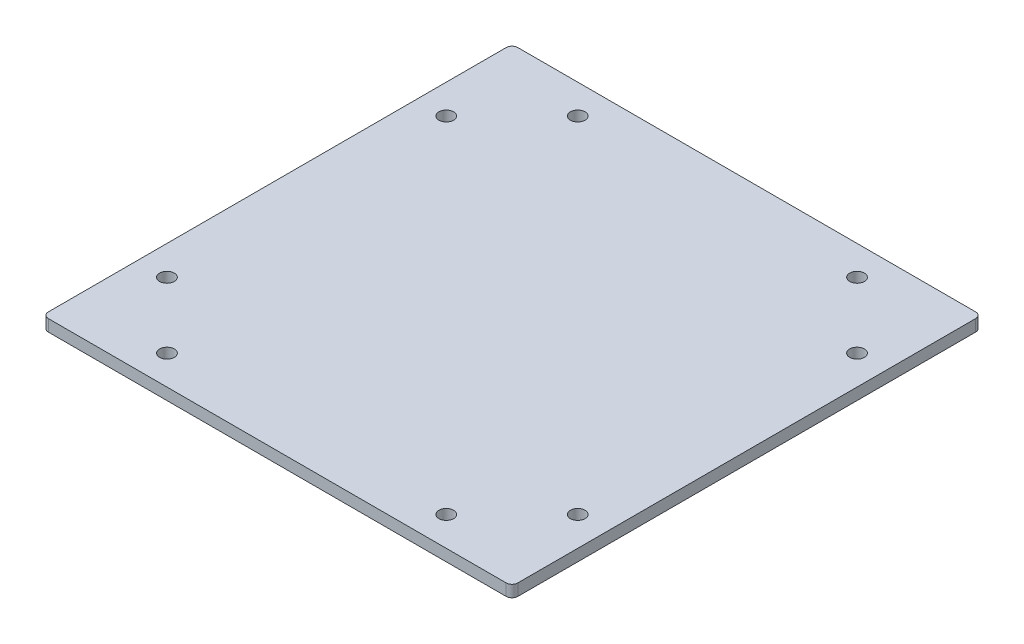
SolidWorks part; units mm, degrees
ref_plane "Front Plane" through (0, 0, 0) normal (0, 0, 1) x (1, 0, 0)
ref_plane "Top Plane" through (0, 0, 0) normal (0, 1, 0) x (1, 0, 0)
ref_plane "Right Plane" through (0, 0, 0) normal (1, 0, 0) x (0, 0, -1)
sketch "Sketch1" plane through (0, 0, 0) normal (0, 1, 0) x (1, 0, 0)
  line L0 (76.2, 101.6) -> (76.2, 76.2) construction
  line L1 (-99.06, -101.6) -> (99.06, -101.6)
  line L2 (-101.6, -99.06) -> (-101.6, 99.06)
  line L3 (-99.06, 101.6) -> (99.06, 101.6)
  line L4 (101.6, -99.06) -> (101.6, 99.06)
  line L5 (-101.6, -101.6) -> (101.6, 101.6) construction
  line L6 (-101.6, 101.6) -> (101.6, -101.6) construction
  line L7 (-101.6, -101.6) -> (-76.2, -101.6) construction
  line L8 (-101.6, -101.6) -> (-101.6, -76.2) construction
  line L9 (-101.6, -76.2) -> (-76.2, -76.2) construction
  line L10 (-76.2, -101.6) -> (-76.2, -76.2) construction
  line L11 (101.6, 76.2) -> (76.2, 76.2) construction
  line L12 (0, -77.4264) -> (0, 21.2334) construction
  line L13 (-76.2, 101.6) -> (-76.2, 76.2) construction
  line L14 (-101.6, 76.2) -> (-76.2, 76.2) construction
  line L15 (101.6, -76.2) -> (76.2, -76.2) construction
  line L16 (76.2, -101.6) -> (76.2, -76.2) construction
  line L17 (-76.2, -88.9) -> (-60.452, -88.9) construction
  circle A0 centre (-60.452, -88.9) radius 3.175
  circle A1 centre (-88.9, -60.452) radius 3.175
  circle A2 centre (88.9, 60.452) radius 3.175
  circle A3 centre (60.452, 88.9) radius 3.175
  circle A4 centre (-60.452, 88.9) radius 3.175
  circle A5 centre (-88.9, 60.452) radius 3.175
  circle A6 centre (60.452, -88.9) radius 3.175
  circle A7 centre (88.9, -60.452) radius 3.175
  arc A8 (-101.6, 99.06) -> (-99.06, 101.6) centre (-99.06, 99.06) cw
  arc A9 (99.06, 101.6) -> (101.6, 99.06) centre (99.06, 99.06) cw
  arc A10 (99.06, -101.6) -> (101.6, -99.06) centre (99.06, -99.06) ccw
  arc A11 (-99.06, -101.6) -> (-101.6, -99.06) centre (-99.06, -99.06) cw
  point P0 (0, 0)
  dimension "D5" = 6.35
  dimension "D7" = 2.54
  dimension "D1" = 203.2
  dimension "D2" = 203.2
  dimension "D3" = 25.4
  dimension "D4" = 15.748
  dimension "D6" = 12.7
extrude "Boss-Extrude1" add sketch "Sketch1" along normal blind 5.08
